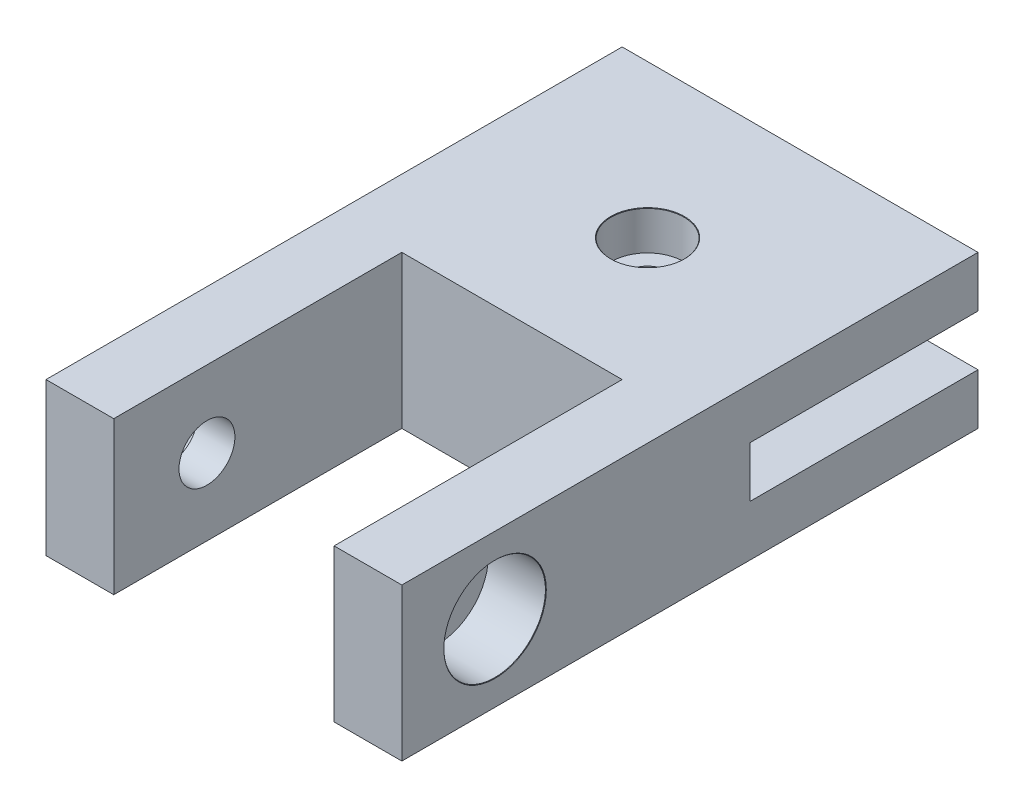
SolidWorks part; units mm, degrees
ref_plane "前视基准面" through (0, 0, 0) normal (0, 0, 1) x (1, 0, 0)
ref_plane "上视基准面" through (0, 0, 0) normal (0, 1, 0) x (1, 0, 0)
ref_plane "右视基准面" through (0, 0, 0) normal (1, 0, 0) x (0, 0, -1)
other "Configuration Table"
sketch "草图1" plane through (0, 0, 0) normal (0, 1, 0) x (1, 0, 0)
  line L1 (-10.5, 17) -> (10.5, 17)
  line L2 (-10.5, 17) -> (-10.5, -17)
  line L3 (-10.5, -17) -> (10.5, -17)
  line L4 (10.5, 17) -> (10.5, -17)
  line L5 (-10.5, 17) -> (10.5, -17) construction
  line L6 (-10.5, -17) -> (10.5, 17) construction
  point P0 (0, 0)
  dimension "D1" = 34
  dimension "D2" = 21
extrude "凸台-拉伸1" add sketch "草图1" along normal blind 9
sketch "草图6" plane through (0, 9, 0) normal (0, 1, 0) x (1, 0, 0)
  line L1 (6.5018, 0) -> (-6.5018, 0)
  line L2 (6.5018, 0) -> (6.5018, -17)
  line L4 (-6.5018, 0) -> (-6.5018, -17)
  line L5 (-10.5, -17) -> (10.5, -17) construction
  line L8 (-6.5018, -17) -> (6.5018, -17)
  point P0 (0, -17)
  dimension "D1" = 17
extrude "切除-拉伸3" cut sketch "草图6" against normal through all
sketch "草图7" plane through (10.5, 0, 0) normal (1, 0, 0) x (0, 0, -1)
  line L0 (-17, 9) -> (-17, 0) construction
  point P0 (-11.5, 4.5)
  point P3 (-17, 4.5)
  dimension "D1" = 5.5
hole_wizard "M3 六角圆柱头螺钉的柱形沉头孔1" positions "草图8" profile "草图9" counterbore size "M3" standard "GB" end condition up to next
sketch "草图8" plane through (10.5, 0, 0) normal (1, 0, 0) x (0, 0, -1)
  point P0 (-11.5, 4.5)
sketch "草图9" plane through (10.5, 4.5, 11.5) normal (0, 1, 0) x (0, 0, -1)
  line L0 (0, 0) -> (0, 3.9982)
  line L1 (0, 3.9982) -> (1.7, 3.9982)
  line L3 (1.7, 3.9982) -> (1.7, 3.4)
  line L4 (3, 3.4) -> (1.7, 3.4)
  line L5 (3, 3.4) -> (3, 0.025)
  line L6 (3, 0.025) -> (3.025, 0)
  line L7 (3.025, 0) -> (0, 0)
  line L8 (-3, 0.025) -> (-3.025, 0) construction
  line L11 (0, -6.35) -> (0, 107.95) construction
  dimension "通孔孔直径" = 3.4
  dimension "通孔孔深度" = 3.9982
  dimension "柱形沉头孔直径" = 6
  dimension "柱形沉头孔深度" = 3.4
  dimension "近端锥形沉头孔直径" = 6.05
  dimension "近端锥形沉头孔角度" = 90
sketch "草图10" plane through (-10.5, 0, 0) normal (-1, 0, 0) x (0, 0, 1)
  line L0 (-17, 0) -> (17, 0) construction
  line L2 (13.1743, 1.6) -> (14.8486, 4.5)
  line L3 (14.8486, 4.5) -> (13.1743, 7.4)
  line L4 (13.1743, 7.4) -> (9.8257, 7.4)
  line L5 (9.8257, 7.4) -> (8.1514, 4.5)
  line L6 (8.1514, 4.5) -> (9.8257, 1.6)
  line L7 (9.8257, 1.6) -> (13.1743, 1.6)
  circle A0 centre (11.5, 4.5) radius 2.9 construction
  dimension "D1" = 5.8
extrude "切除-拉伸4" cut sketch "草图10" against normal blind 1.8
sketch "草图11" plane through (-8.7, 0, 0) normal (-1, 0, 0) x (0, 0, 1)
  circle A0 centre (11.5, 4.5) radius 1.65
  dimension "D1" = 3.3
extrude "切除-拉伸5" cut sketch "草图11" against normal up to next
ref_plane "基准面1" through (0, 3, 0) normal (0, -1, 0) x (-1, 0, 0)
sketch "草图12" plane through (0, 3, 0) normal (0, -1, 0) x (-1, 0, 0)
  line L0 (10.5, 17) -> (10.5, -17) construction
  line L1 (-10.5, 17) -> (10.5, 17)
  line L2 (-10.5, 17) -> (-10.5, 3.5528)
  line L3 (-10.5, 3) -> (10.5, 3) construction
  line L4 (10.5, 17) -> (10.5, 3.5528)
  line L5 (-6.5018, 0) -> (6.5018, 0) construction
  arc A0 (-10.5, 3.5528) -> (10.5, 3.5528) centre (0, 103) ccw
  dimension "D2" = 200
  dimension "D1" = 3
  dimension "D3" = 21
extrude "切除-拉伸6" cut sketch "草图12" against normal blind 3
sketch "草图13" plane through (0, 9, 0) normal (0, 1, 0) x (1, 0, 0)
  line L0 (0, 103) -> (0, 8) construction
  line L3 (10.5, 17) -> (-10.5, 17)
  line L4 (-10.5, 17) -> (-10.5, 3.5528)
  line L5 (10.5, 3.5528) -> (10.5, 17)
  arc A1 (-10.5, 3.5528) -> (10.5, 3.5528) centre (0, 103) ccw
  arc A2 (-10.5, 3.5528) -> (10.5, 3.5528) centre (0, 103) ccw
  dimension "D2" = 95
  dimension "D1" = 0
hole_wizard "M2 六角圆柱头螺钉的柱形沉头孔1" positions "草图14" profile "草图15" counterbore size "M2" standard "GB" end condition up to next
sketch "草图14" plane through (0, 9, 0) normal (0, 1, 0) x (1, 0, 0)
  point P0 (0, 8)
sketch "草图15" plane through (0, 9, -8) normal (1, 0, 0) x (0, 0, 1)
  line L0 (0, 0) -> (0, 3)
  line L1 (0, 3) -> (1.2, 3)
  line L3 (1.2, 3) -> (1.2, 2.3)
  line L4 (2.15, 2.3) -> (1.2, 2.3)
  line L5 (2.15, 2.3) -> (2.15, 0.025)
  line L6 (2.15, 0.025) -> (2.175, 0)
  line L7 (2.175, 0) -> (0, 0)
  line L8 (-2.15, 0.025) -> (-2.175, 0) construction
  line L11 (0, -6.35) -> (0, 107.95) construction
  dimension "通孔孔直径" = 2.4
  dimension "通孔孔深度" = 3
  dimension "柱形沉头孔直径" = 4.3
  dimension "柱形沉头孔深度" = 2.3
  dimension "近端锥形沉头孔直径" = 4.35
  dimension "近端锥形沉头孔角度" = 90
sketch "草图16" plane through (0, 3, 0) normal (0, 1, 0) x (1, 0, 0)
  arc A0 (-10.5, 3.5528) -> (10.5, 3.5528) centre (0, 103) ccw construction
  arc A1 (-10.5, 3.5528) -> (10.5, 3.5528) centre (0, 103) ccw
  circle A2 centre (0, 8) radius 1.2
  dimension "D1" = 2.4
extrude "切除-拉伸7" cut sketch "草图16" against normal up to next contours A2
sketch "草图17" plane through (0, 0, 0) normal (0, -1, 0) x (1, 0, 0)
  line L0 (6.5018, 0) -> (-6.5018, 0) construction
  line L1 (1.2124, -10.1) -> (2.4249, -8)
  line L2 (2.4249, -8) -> (1.2124, -5.9)
  line L3 (1.2124, -5.9) -> (-1.2124, -5.9)
  line L4 (-1.2124, -5.9) -> (-2.4249, -8)
  line L5 (-2.4249, -8) -> (-1.2124, -10.1)
  line L6 (-1.2124, -10.1) -> (1.2124, -10.1)
  circle A0 centre (0, -8) radius 2.1 construction
  dimension "D1" = 4.2
extrude "切除-拉伸8" cut sketch "草图17" against normal blind 1.8
